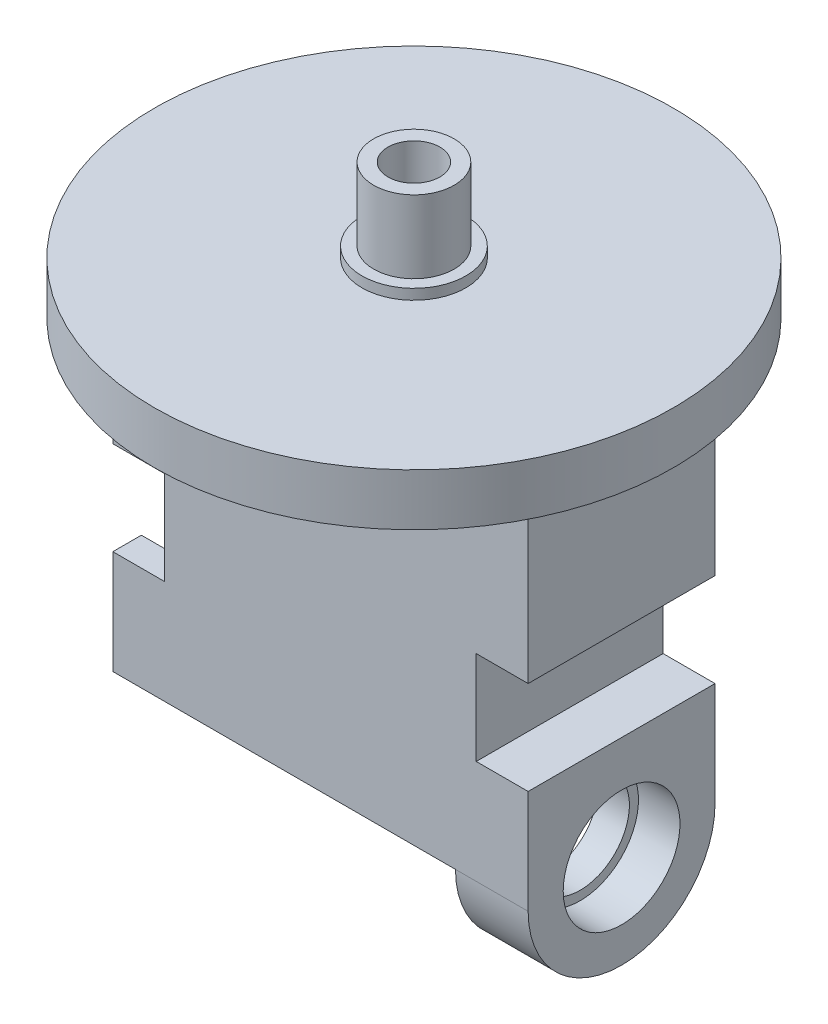
SolidWorks part; units mm, degrees
ref_plane "Front Plane" through (0, 0, 0) normal (0, 0, 1) x (1, 0, 0)
ref_plane "Top Plane" through (0, 0, 0) normal (0, 1, 0) x (1, 0, 0)
ref_plane "Right Plane" through (0, 0, 0) normal (1, 0, 0) x (0, 0, -1)
sketch "Sketch1" plane through (0, 0, 0) normal (0, 1, 0) x (1, 0, 0)
  line L5 (0, 25) -> (0, -25) construction
  line L6 (-25, 0) -> (25, 0) construction
  circle A2 centre (0, 0) radius 25
  dimension "D1" = 50
extrude "Boss-Extrude1" add sketch "Sketch1" along normal blind 5
ref_plane "Plane3" through (20, 0, 0) normal (1, 0, 0) x (0, 0, -1)
sketch "Sketch8" plane through (20, 0, 0) normal (1, 0, 0) x (0, 0, -1)
  line L0 (0, 0) -> (0, -35) construction
  line L3 (-9, 0) -> (-9, -35)
  line L4 (-9, 0) -> (9, 0)
  line L6 (9, 0) -> (9, -35)
  line L7 (-9, 0) -> (9, -35) construction
  line L8 (-9, -35) -> (9, 0) construction
  circle A5 centre (0, -35) radius 4.75
  arc A11 (-9, -35) -> (9, -35) centre (0, -35) ccw
  point P5 (0, -17.5)
  dimension "D2" = 18
  dimension "D4" = 9.5
  dimension "D1" = 35
extrude "Boss-Extrude3" add sketch "Sketch8" against normal blind 7
sketch "Sketch9" plane through (20, 0, 0) normal (-1, 0, 0) x (0, 0, 1)
  circle A0 centre (0, -35) radius 5.625
  dimension "D1" = 11.25
extrude "Cut-Extrude3" cut sketch "Sketch9" along normal blind 4
sketch "Sketch10" plane through (0, 0, 0) normal (0, -1, 0) x (-1, 0, 0)
  line L0 (0, -9) -> (0, 9) construction
  line L1 (-20, 9) -> (20, 9)
  line L2 (-20, 9) -> (-20, -9)
  line L3 (-20, -9) -> (20, -9)
  line L4 (20, 9) -> (20, -9)
sketch "Sketch11" plane through (0, 0, 0) normal (0, -1, 0) x (-1, 0, 0)
  line L1 (-13, -9) -> (20, -9)
  line L2 (-13, -9) -> (-13, 9)
  line L3 (-13, 9) -> (20, 9)
  line L4 (20, -9) -> (20, 9)
extrude "Boss-Extrude4" add sketch "Sketch11" along normal up to vertex (35 mm away)
sketch "Sketch12" plane through (-20, 0, 0) normal (-1, 0, 0) x (0, 0, 1)
  line L0 (9, -35) -> (-9, -35) construction
  line L1 (6.25, -35) -> (-6.25, -35)
  line L2 (6.25, -35) -> (6.25, -17)
  line L3 (6.25, -17) -> (-6.25, -17)
  line L4 (-6.25, -35) -> (-6.25, -17)
  line L5 (0, -17) -> (0, 0) construction
  dimension "D1" = 18
  dimension "D2" = 12.5
extrude "Cut-Extrude4" cut sketch "Sketch12" against normal blind 28
sketch "Sketch13" plane through (-20, 0, 0) normal (-1, 0, 0) x (0, 0, 1)
  line L1 (6.25, -17) -> (-6.25, -17)
  line L2 (6.25, -17) -> (6.25, -11)
  line L3 (6.25, -11) -> (-6.25, -11)
  line L4 (-6.25, -17) -> (-6.25, -11)
  dimension "D1" = 6
extrude "Cut-Extrude6" cut sketch "Sketch13" against normal offset from surface (10.79 mm away) 17.21 up to face at (8, -26, 0)
ref_plane "Plane4" through (0, 0, 0) normal (-1, 0, 0) x (0, 0, 1)
sketch "Sketch15" plane through (-20, 0, 0) normal (-1, 0, 0) x (0, 0, 1)
  line L0 (-6.25, -11) -> (-6.25, -35) construction
  line L1 (-6.25, -25) -> (-9, -25)
  line L3 (-6.25, -16) -> (-9, -16)
  line L4 (-9, -25) -> (-9, -16)
  line L5 (-9, -35) -> (-9, 0) construction
  line L6 (0, -11) -> (0, -35.5511) construction
  line L7 (6.25, -11) -> (-6.25, -11) construction
  line L8 (-6.25, -25) -> (9, -25)
  line L9 (9, -35) -> (9, 0) construction
  line L10 (9, -25) -> (9, -16)
  line L11 (9, -16) -> (-6.25, -16)
  dimension "D1" = 14
  dimension "D2" = 9
extrude "Cut-Extrude8" cut sketch "Sketch15" against normal blind 5
mirror "Mirror1" about plane through (0, 0, 0) normal (-1, 0, 0) of "Cut-Extrude8"
sketch "Sketch16" plane through (0, 5, 0) normal (0, 1, 0) x (1, 0, 0)
  circle A0 centre (0, 0) radius 5
  dimension "D1" = 10
extrude "Boss-Extrude5" add sketch "Sketch16" along normal blind 1
sketch "Sketch17" plane through (0, 6, 0) normal (0, 1, 0) x (1, 0, 0)
  circle A0 centre (0, 0) radius 3.875
  dimension "D1" = 7.75
extrude "Boss-Extrude6" add sketch "Sketch17" along normal blind 7
sketch "Sketch18" plane through (0, 13, 0) normal (0, 1, 0) x (1, 0, 0)
  circle A0 centre (0, 0) radius 2.5
  dimension "D1" = 5
extrude "Cut-Extrude9" cut sketch "Sketch18" against normal blind 6 contours A0
sketch "Sketch14" plane through (0, 5, 0) normal (0, 1, 0) x (1, 0, 0)
  circle A0 centre (0, 0) radius 3
  dimension "D1" = 6
extrude "Cut-Extrude7" cut sketch "Sketch14" against normal blind 7
